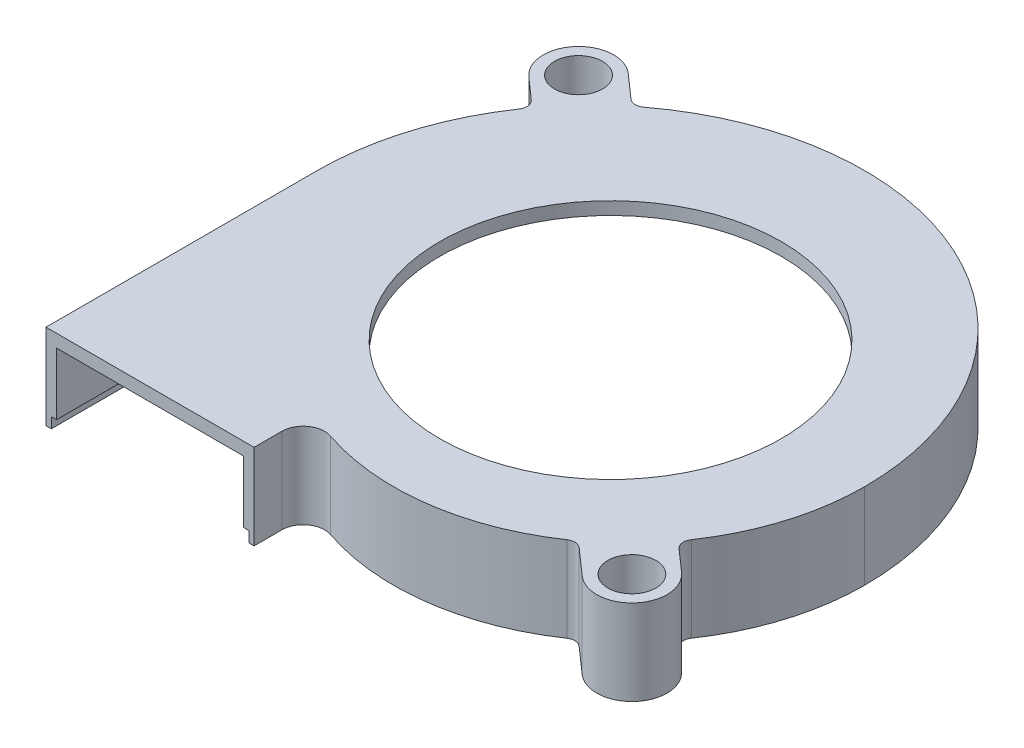
SolidWorks part; units mm, degrees
material "PET"
ref_plane "Спереди" through (0, 0, 0) normal (0, 0, 1) x (1, 0, 0)
ref_plane "Сверху" through (0, 0, 0) normal (0, 1, 0) x (1, 0, 0)
ref_plane "Справа" through (0, 0, 0) normal (1, 0, 0) x (0, 0, -1)
sketch "Эскиз1" plane through (0, 0, 0) normal (0, 1, 0) x (1, 0, 0)
  line L0 (0, -37.0288) -> (0, 52.769) construction
  line L1 (-41.2177, 0) -> (28.9689, 0) construction
  line L2 (-27.5, -25.4) -> (-8, -25.4)
  line L3 (-8, -25.4) -> (-8, -22.7923)
  line L4 (-27.5, -25.4) -> (-27.5, 0)
  line L5 (17.8147, -20.4728) -> (22.1853, -15.5272) construction
  line L6 (-25.1853, 17.5272) -> (-20.8147, 22.4728) construction
  line L7 (-23, 20) -> (20, -18) construction
  line L8 (-20.8147, 22.4728) -> (-18.5989, 20.5146)
  line L9 (-25.1853, 17.5272) -> (-23.2069, 15.7789)
  line L10 (17.8147, -20.4728) -> (15.377, -18.3185)
  line L11 (22.1853, -15.5272) -> (20.1437, -13.7231)
  circle A0 centre (0, 0) radius 16
  arc A1 (23.8, 0) -> (-17.3331, 20.4667) centre (-1.85, 0.0168) ccw
  circle A2 centre (-23, 20) radius 2.25
  circle A3 centre (20, -18) radius 2.25
  arc A4 (23.8, 0) -> (19.9791, -12.4113) centre (1.7319, 0) cw
  arc A5 (22.1853, -15.5272) -> (17.8147, -20.4728) centre (20, -18) cw
  arc A6 (-25.1853, 17.5272) -> (-20.8147, 22.4728) centre (-23, 20) cw
  arc A7 (14.152, -18.2412) -> (-5.3575, -20.8983) centre (1.7319, 0) cw
  arc A8 (-23.0428, 14.4662) -> (-27.5, 0) centre (-1.85, 0.0168) ccw
  arc A9 (-5.3575, -20.8983) -> (-8, -22.7923) centre (-6, -22.7923) ccw
  arc A10 (-18.5989, 20.5146) -> (-17.3331, 20.4667) centre (-17.9367, 21.2639) ccw
  arc A11 (-23.2069, 15.7789) -> (-23.0428, 14.4662) centre (-23.8691, 15.0296) cw
  arc A12 (20.1437, -13.7231) -> (19.9791, -12.4113) centre (20.8059, -12.9738) cw
  arc A13 (15.377, -18.3185) -> (14.152, -18.2412) centre (14.7148, -19.0678) ccw
  point P14 (0, 25.6)
  point P16 (16, 0)
  point P17 (0, -22)
  point P20 (23.8, 0)
  point P26 (0, -16)
  point P34 (-22.5346, 15.1848)
  point P41 (14.784, -17.7945)
  dimension "D1" = 18
  dimension "D2" = 20
  dimension "D8" = 51
  dimension "D11" = 3.3
  dimension "D12" = 7.8
  dimension "D13" = 6
  dimension "D14" = 2
  dimension "D5" = 4.5
  dimension "D6" = 32
  dimension "D15" = 1
  dimension "D3" = 23
  dimension "D4" = 20
  dimension "D7" = 51.3
  dimension "D9" = 19.5
  dimension "D10" = 25.4
extrude "Бобышка-Вытянуть1" add sketch "Эскиз1" against normal blind 8
sketch "Эскиз2" plane through (0, -8, 0) normal (0, -1, 0) x (-1, 0, 0)
  line L12 (8, -25.4) -> (8, -22.7923) construction
  line L13 (27.5, 0) -> (27.5, -25.4) construction
  line L14 (8, -25.4) -> (8, -22.7923) construction
  line L15 (27.5, 0) -> (27.5, -25.4) construction
  line L16 (9, -25.4) -> (9, -22.7923)
  line L17 (26.5, 0.0003) -> (26.5, -25.4)
  line L18 (26.5, -25.4) -> (9, -25.4)
  arc A19 (17.3331, 20.4667) -> (-23.8, 0) centre (1.85, 0.0168) ccw construction
  arc A20 (-23.8, 0) -> (-19.9791, -12.4113) centre (-1.7319, 0) ccw construction
  arc A21 (-14.152, -18.2412) -> (5.3575, -20.8983) centre (-1.7319, 0) ccw construction
  arc A22 (8, -22.7923) -> (5.3575, -20.8983) centre (6, -22.7923) ccw construction
  arc A23 (27.5, 0) -> (23.0428, 14.4662) centre (1.85, 0.0168) ccw construction
  arc A24 (17.3331, 20.4667) -> (-23.8, 0) centre (1.85, 0.0168) ccw construction
  arc A25 (-23.8, 0) -> (-19.9791, -12.4113) centre (-1.7319, 0) ccw construction
  arc A26 (-14.152, -18.2412) -> (5.3575, -20.8983) centre (-1.7319, 0) ccw construction
  arc A27 (8, -22.7923) -> (5.3575, -20.8983) centre (6, -22.7923) ccw construction
  arc A28 (27.5, 0) -> (23.0428, 14.4662) centre (1.85, 0.0168) ccw construction
  arc A29 (17.3331, 20.4667) -> (23.0428, 14.4662) centre (1.85, 0.0168) cw construction
  arc A30 (-19.9791, -12.4113) -> (-14.152, -18.2412) centre (-1.7319, 0) ccw construction
  arc A31 (9, -22.7923) -> (5.0362, -19.9513) centre (6, -22.7923) ccw
  arc A32 (-13.5892, -17.4146) -> (5.0362, -19.9513) centre (-1.7319, 0) ccw
  arc A33 (-19.1522, -11.8489) -> (-13.5892, -17.4146) centre (-1.7319, 0) ccw
  arc A34 (-22.8, 0.0003) -> (-19.1522, -11.8489) centre (-1.7319, 0) ccw
  arc A35 (16.7295, 19.6694) -> (-22.8, 0.0003) centre (1.85, 0.0168) ccw
  arc A36 (16.7295, 19.6694) -> (22.2166, 13.9029) centre (1.85, 0.0168) cw
  arc A37 (26.5, 0.0003) -> (22.2166, 13.9029) centre (1.85, 0.0168) ccw
  dimension "D1" = 1
extrude "Вырез-Вытянуть1" cut sketch "Эскиз2" against normal offset from surface (6.8 mm away) 1.2 up to face at (0, 0, 16)
sketch "Эскиз11" plane through (0, -8, 0) normal (0, -1, 0) x (1, 0, 0)
  line L0 (-9, 22.7923) -> (-9, 25.4) construction
  line L1 (-26.5, 25.4) -> (-26.5, -0.0003) construction
  line L2 (-9, 22.7923) -> (-9, 25.4)
  line L3 (-26.5, 25.4) -> (-26.5, -0.0003)
  line L4 (-27, 25.4) -> (-27, -0.0002)
  line L5 (-8.5, 22.7923) -> (-8.5, 25.4)
  line L6 (-27, 25.4) -> (-26.5, 25.4)
  line L7 (-9, 25.4) -> (-8.5, 25.4)
  arc A0 (-9, 22.7923) -> (-5.0362, 19.9513) centre (-6, 22.7923) ccw construction
  arc A1 (22.8, -0.0003) -> (-5.0362, 19.9513) centre (1.7319, 0) ccw construction
  arc A2 (-26.5, -0.0003) -> (22.8, -0.0003) centre (-1.85, -0.0168) ccw construction
  arc A3 (-9, 22.7923) -> (-5.0362, 19.9513) centre (-6, 22.7923) ccw
  arc A4 (22.8, -0.0003) -> (-5.0362, 19.9513) centre (1.7319, 0) ccw
  arc A5 (-26.5, -0.0003) -> (22.8, -0.0003) centre (-1.85, -0.0168) ccw
  arc A6 (-27, -0.0002) -> (23.3, -0.0001) centre (-1.85, -0.0168) ccw
  arc A7 (23.3, -0.0001) -> (-5.1969, 20.4248) centre (1.7319, 0) ccw
  arc A8 (-8.5, 22.7923) -> (-5.1969, 20.4248) centre (-6, 22.7923) ccw
  dimension "D1" = 0.5
extrude "Вырез-Вытянуть8" cut sketch "Эскиз11" against normal blind 1
